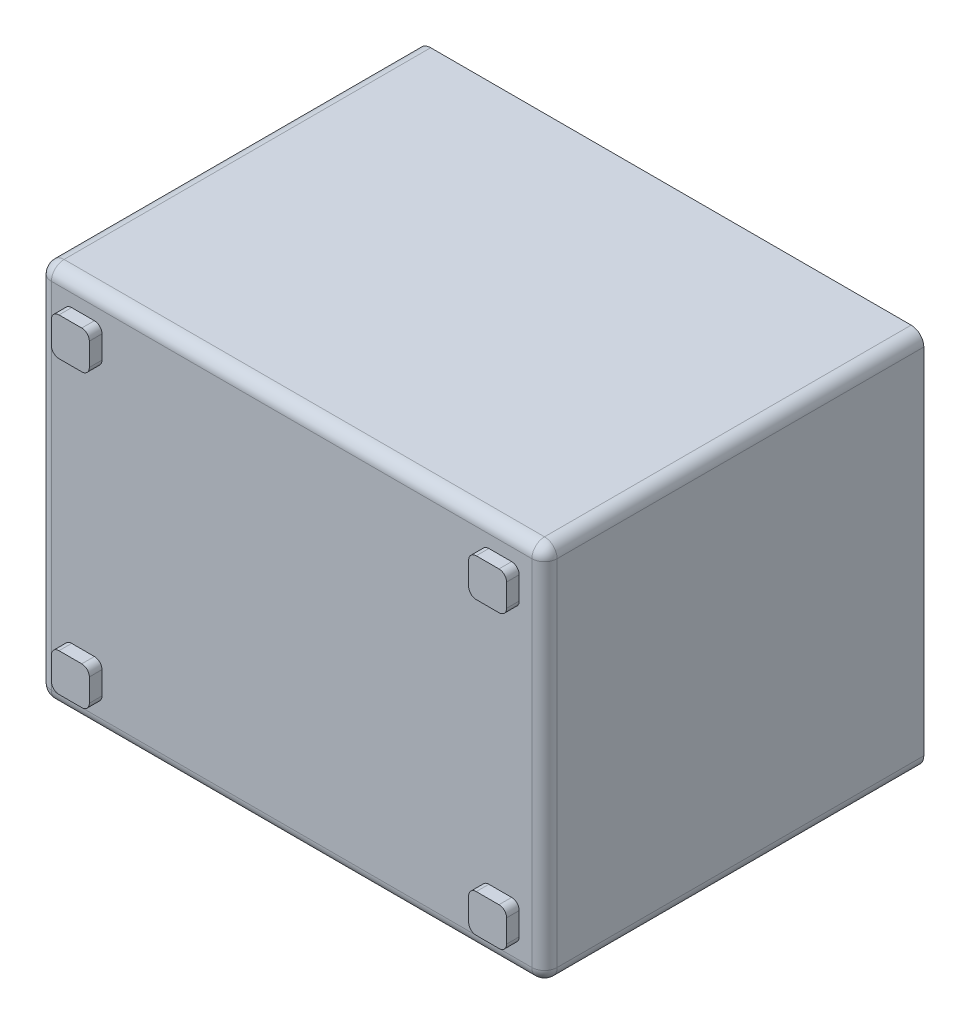
SolidWorks part; units mm, degrees
ref_plane "Front Plane" through (0, 0, 0) normal (0, 0, 1) x (1, 0, 0)
ref_plane "Top Plane" through (0, 0, 0) normal (0, 1, 0) x (1, 0, 0)
ref_plane "Right Plane" through (0, 0, 0) normal (1, 0, 0) x (0, 0, -1)
sketch "Sketch1" plane through (0, 0, 0) normal (0, 0, 1) x (1, 0, 0)
  line L1 (-67.7557, 30.0426) -> (132.2443, 30.0426)
  line L2 (-67.7557, 30.0426) -> (-67.7557, -119.9574)
  line L3 (-67.7557, -119.9574) -> (132.2443, -119.9574)
  line L4 (132.2443, 30.0426) -> (132.2443, -119.9574)
  dimension "D1" = 200
  dimension "D2" = 150
extrude "Boss-Extrude1" add sketch "Sketch1" along normal blind 150
sketch "Sketch2" plane through (0, 0, 0) normal (0, 0, 1) x (1, 0, 0)
  line L0 (-67.7557, 30.0426) -> (-67.7557, -119.9574) construction
  line L1 (-62.7557, 25.0426) -> (127.2443, 25.0426)
  line L2 (-62.7557, 25.0426) -> (-62.7557, -114.9574)
  line L3 (-62.7557, -114.9574) -> (127.2443, -114.9574)
  line L4 (127.2443, 25.0426) -> (127.2443, -114.9574)
  line L5 (-67.7557, -119.9574) -> (132.2443, -119.9574) construction
  line L6 (132.2443, -119.9574) -> (132.2443, 30.0426) construction
  line L7 (132.2443, 30.0426) -> (-67.7557, 30.0426) construction
  dimension "D1" = 5
  dimension "D2" = 5
  dimension "D3" = 5
  dimension "D4" = 5
extrude "Cut-Extrude1" cut sketch "Sketch2" along normal blind 145
sketch "Sketch3" plane through (0, 0, 150) normal (0, 0, 1) x (1, 0, 0)
  line L0 (-67.7557, 30.0426) -> (-67.7557, -119.9574) construction
  line L1 (-57.7557, 20.0426) -> (-42.7557, 20.0426)
  line L2 (-57.7557, 20.0426) -> (-57.7557, 5.0426)
  line L3 (-57.7557, 5.0426) -> (-42.7557, 5.0426)
  line L4 (-42.7557, 20.0426) -> (-42.7557, 5.0426)
  line L5 (132.2443, 30.0426) -> (-67.7557, 30.0426) construction
  line L6 (32.2443, 30.0426) -> (32.2443, -119.9574)
  line L7 (-67.7557, -119.9574) -> (132.2443, -119.9574) construction
  line L8 (-67.7557, -44.9574) -> (132.2443, -44.9574)
  line L9 (132.2443, -119.9574) -> (132.2443, 30.0426) construction
  line L10 (122.2443, 5.0426) -> (107.2443, 5.0426)
  line L11 (122.2443, 20.0426) -> (107.2443, 20.0426)
  line L12 (122.2443, 20.0426) -> (122.2443, 5.0426)
  line L13 (107.2443, 20.0426) -> (107.2443, 5.0426)
  line L14 (107.2443, -109.9574) -> (107.2443, -94.9574)
  line L15 (122.2443, -109.9574) -> (122.2443, -94.9574)
  line L16 (122.2443, -109.9574) -> (107.2443, -109.9574)
  line L17 (122.2443, -94.9574) -> (107.2443, -94.9574)
  line L18 (-42.7557, -109.9574) -> (-42.7557, -94.9574)
  line L19 (-57.7557, -94.9574) -> (-42.7557, -94.9574)
  line L20 (-57.7557, -109.9574) -> (-57.7557, -94.9574)
  line L21 (-57.7557, -109.9574) -> (-42.7557, -109.9574)
  dimension "D1" = 15
  dimension "D2" = 15
  dimension "D3" = 10
  dimension "D4" = 10
extrude "Boss-Extrude3" add sketch "Sketch3" along normal blind 5 contours L4 L1 L2 L3 | L11 L13 L10 L12 | L20 L21 L18 L19 | L15 L17 L14 L16
fillet "Fillet1" radius 5 8 edges at (32.2443, -119.9574, 150) (-67.7557, -44.9574, 150) (-67.7557, 30.0426, 75) (132.2443, 30.0426, 75) (132.2443, -44.9574, 150) (-67.7557, -119.9574, 75) (132.2443, -119.9574, 75) (32.2443, 30.0426, 150)
fillet "Fillet2" radius 3 16 edges at (-42.7557, 20.0426, 152.5) (-42.7557, 5.0426, 152.5) (-42.7557, -109.9574, 152.5) (-42.7557, -94.9574, 152.5) (-57.7557, -94.9574, 152.5) (-57.7557, -109.9574, 152.5) (-57.7557, 5.0426, 152.5) (-57.7557, 20.0426, 152.5) (122.2443, 5.0426, 152.5) (107.2443, 5.0426, 152.5) (122.2443, 20.0426, 152.5) (107.2443, 20.0426, 152.5) (107.2443, -109.9574, 152.5) (107.2443, -94.9574, 152.5) (122.2443, -109.9574, 152.5) (122.2443, -94.9574, 152.5)
